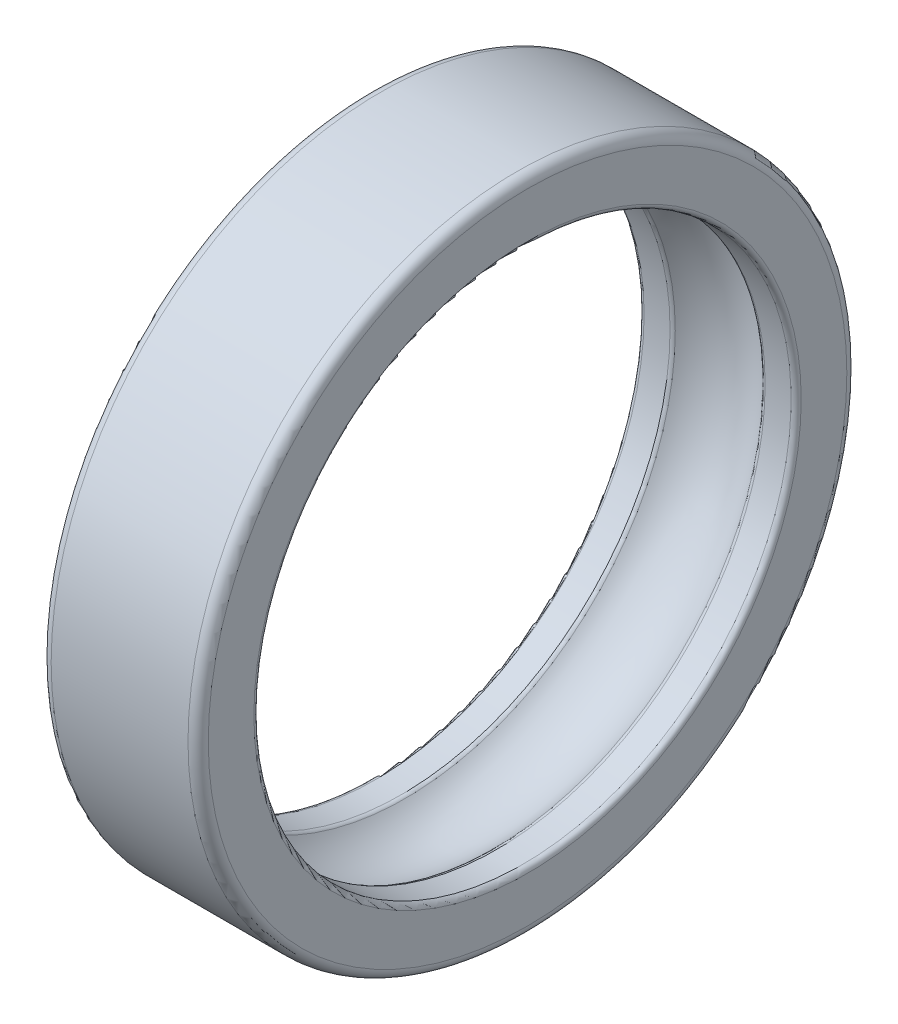
SolidWorks part; units mm, degrees
ref_plane "Front Plane" through (0, 0, 0) normal (0, 0, 1) x (1, 0, 0)
ref_plane "Top Plane" through (0, 0, 0) normal (0, 1, 0) x (1, 0, 0)
ref_plane "Right Plane" through (0, 0, 0) normal (1, 0, 0) x (0, 0, -1)
sketch "Sketch1" plane through (0, 0, 0) normal (0, 0, 1) x (1, 0, 0)
  line L0 (0, 0) -> (0, -24.5033) construction
  line L1 (0, 0) -> (24.5033, 0) construction
  line L2 (8.9443, 53) -> (15.5, 53)
  line L3 (-13.5, 65) -> (13.5, 65)
  line L4 (-15.5, 63) -> (-15.5, 53)
  line L5 (-15.5, 53) -> (-8.9443, 53)
  line L6 (15.5, 63) -> (15.5, 53)
  arc A0 (8.9443, 53) -> (-8.9443, 53) centre (0, 45) ccw
  arc A1 (13.5, 65) -> (15.5, 63) centre (13.5, 63) cw
  arc A2 (-13.5, 65) -> (-15.5, 63) centre (-13.5, 63) ccw
  point P12 (0, 0)
  point P15 (15.5, 65)
  point P18 (-15.5, 65)
  dimension "D5" = 12
  dimension "D6" = 2
  dimension "D1" = 106
  dimension "D2" = 130
  dimension "D3" = 31
  dimension "D4" = 8
revolve "Revolve1" add sketch "Sketch1" angle 360 about L1
fillet "Fillet1" radius 1 4 edges at (8.9443, 0, 53) (15.5, 0, 53) (-15.5, 0, 53) (-8.9443, 0, 53)
